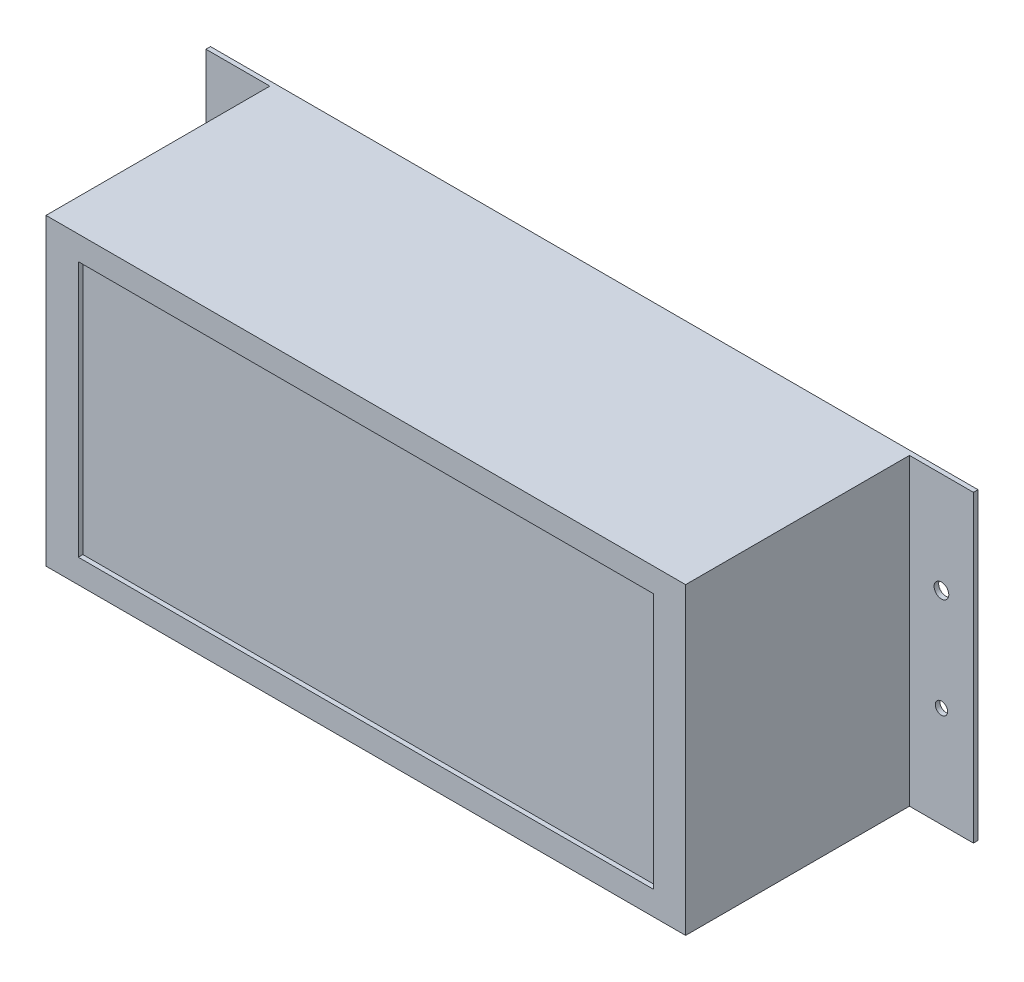
SolidWorks part; units mm, degrees
ref_plane "Alzado" through (0, 0, 0) normal (0, 0, 1) x (1, 0, 0)
ref_plane "Planta" through (0, 0, 0) normal (0, 1, 0) x (1, 0, 0)
ref_plane "Vista lateral" through (0, 0, 0) normal (1, 0, 0) x (0, 0, -1)
sketch "Croquis1" plane through (0, 0, 0) normal (0, 0, 1) x (1, 0, 0)
  line L1 (-140, 66.5) -> (140, 66.5)
  line L2 (-140, 66.5) -> (-140, -66.5)
  line L3 (-140, -66.5) -> (140, -66.5)
  line L4 (140, 66.5) -> (140, -66.5)
  line L5 (-140, 66.5) -> (140, -66.5) construction
  line L6 (-140, -66.5) -> (140, 66.5) construction
  point P0 (0, 0)
  dimension "D1" = 280
  dimension "D2" = 133
extrude "Saliente-Extruir1" add sketch "Croquis1" along normal blind 100
sketch "Croquis2" plane through (0, 0, 0) normal (0, 0, -1) x (-1, 0, 0)
  line L0 (-140, 66.5) -> (-168, 66.5)
  line L1 (-140, -66.5) -> (-168, -66.5)
  line L2 (-168, -66.5) -> (-168, 66.5)
  line L3 (-140, 66.5) -> (-154, 66.5) construction
  line L4 (-154, 66.5) -> (-154, 22.27) construction
  line L5 (-154, 22.27) -> (-154, -22.32) construction
  line L6 (0, 0) -> (0, 49.185) construction
  line L7 (154, 22.27) -> (154, -22.32) construction
  line L8 (154, 66.5) -> (154, 22.27) construction
  line L9 (140, 66.5) -> (154, 66.5) construction
  line L10 (168, -66.5) -> (168, 66.5)
  line L11 (140, -66.5) -> (168, -66.5)
  line L12 (140, 66.5) -> (168, 66.5)
  line L13 (-140, 66.5) -> (-140, -66.5)
  line L14 (140, -66.5) -> (140, 66.5)
  circle A0 centre (-154, 22.27) radius 3.2192
  circle A1 centre (-154, -22.32) radius 2.685
  circle A2 centre (154, -22.32) radius 2.685
  circle A3 centre (154, 22.27) radius 3.2192
  dimension "D1" = 28
  dimension "D2" = 14
  dimension "D3" = 44.23
  dimension "D4" = 44.59
extrude "Saliente-Extruir2" add sketch "Croquis2" against normal blind 2
sketch "Croquis5" plane through (0, 0, 100) normal (0, 0, 1) x (1, 0, 0)
  line L1 (125.8586, -56.033) -> (-125.8586, -56.033)
  line L2 (125.8586, -56.033) -> (125.8586, 56.033)
  line L3 (125.8586, 56.033) -> (-125.8586, 56.033)
  line L4 (-125.8586, -56.033) -> (-125.8586, 56.033)
  line L5 (125.8586, -56.033) -> (-125.8586, 56.033) construction
  line L6 (125.8586, 56.033) -> (-125.8586, -56.033) construction
  point P0 (0, 0)
extrude "Cortar-Extruir5" cut sketch "Croquis5" against normal blind 2
sketch "Croquis6" plane through (0, -66.5, 0) normal (0, -1, 0) x (1, 0, 0)
  line L0 (93.6756, 68.9143) -> (-110.9165, 68.9143) construction
  text T0 "sedpc" font "Century Gothic" height in points 200
extrude "Saliente-Extruir3" add sketch "Croquis6" along normal blind 2
sketch "Croquis8" plane through (0, 0, 0) normal (0, 0, -1) x (-1, 0, 0)
  line L0 (168, -66.5) -> (-168, -66.5) construction
  line L1 (140, 56.5) -> (-140, 56.5)
  line L2 (140, 56.5) -> (140, -56.5)
  line L3 (140, -56.5) -> (-140, -56.5)
  line L4 (-140, 56.5) -> (-140, -56.5)
  line L5 (140, 56.5) -> (-140, -56.5) construction
  line L6 (140, -56.5) -> (-140, 56.5) construction
  point P0 (0, 0)
  dimension "D1" = 280
  dimension "D2" = 10
extrude "Cortar-Extruir8" cut sketch "Croquis8" against normal blind 1
